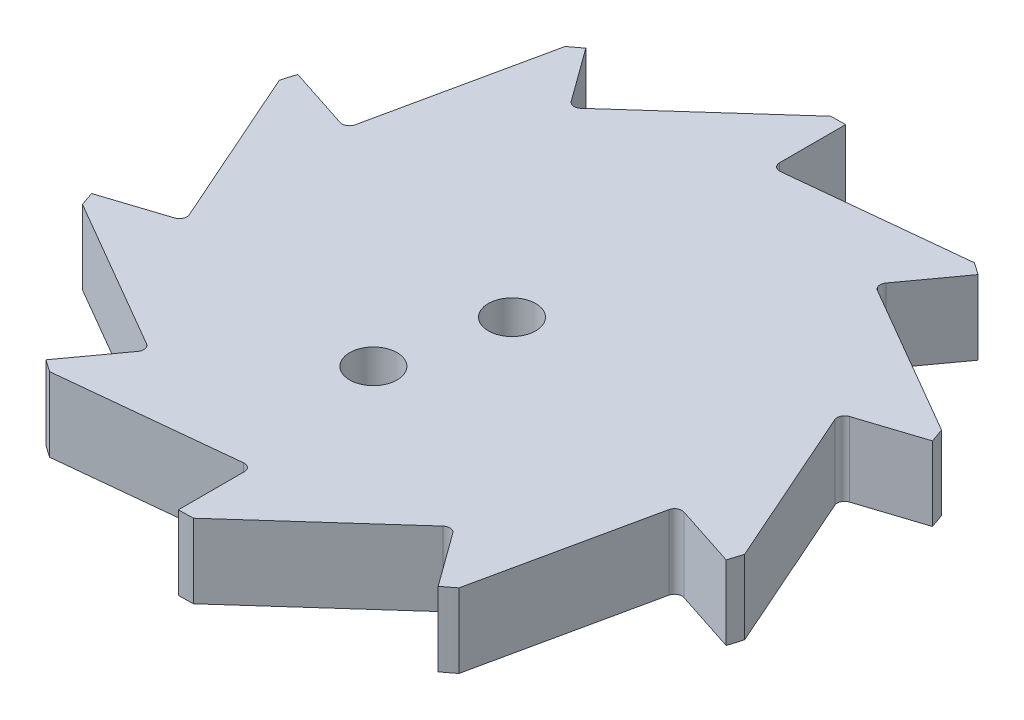
SolidWorks part; units mm, degrees
ref_plane "Front Plane" through (0, 0, 0) normal (0, 0, 1) x (1, 0, 0)
ref_plane "Top Plane" through (0, 0, 0) normal (0, 1, 0) x (1, 0, 0)
ref_plane "Right Plane" through (0, 0, 0) normal (1, 0, 0) x (0, 0, -1)
sketch "Sketch2" plane through (0, 0, 0) normal (0, 1, 0) x (1, 0, 0)
  line L0 (0, 35) -> (0, 45)
  line L1 (-20.5725, 28.3156) -> (0, 0) construction
  line L2 (0, 0) -> (0, 49.5121) construction
  line L3 (-20.5725, 28.3156) -> (-2, 44.9555)
  line L4 (20.5725, 28.3156) -> (26.4503, 36.4058)
  line L5 (0, 35) -> (24.8062, 37.5454)
  line L6 (33.287, 10.8156) -> (42.7975, 13.9058)
  line L7 (20.5725, 28.3156) -> (42.1372, 15.7941)
  line L8 (33.287, -10.8156) -> (42.7975, -13.9058)
  line L9 (33.287, 10.8156) -> (43.3733, -11.9899)
  line L10 (20.5725, -28.3156) -> (26.4503, -36.4058)
  line L11 (33.287, -10.8156) -> (28.0422, -35.1942)
  line L12 (0, -35) -> (0, -45)
  line L13 (20.5725, -28.3156) -> (2, -44.9555)
  line L14 (-20.5725, -28.3156) -> (-26.4503, -36.4058)
  line L15 (0, -35) -> (-24.8062, -37.5454)
  line L16 (-33.287, -10.8156) -> (-42.7975, -13.9058)
  line L17 (-20.5725, -28.3156) -> (-42.1372, -15.7941)
  line L18 (-33.287, 10.8156) -> (-42.7975, 13.9058)
  line L19 (-33.287, -10.8156) -> (-43.3733, 11.9899)
  line L20 (-20.5725, 28.3156) -> (-26.4503, 36.4058)
  line L21 (-33.287, 10.8156) -> (-28.0422, 35.1942)
  circle A0 centre (0, 0) radius 35
  arc A1 (-2, 44.9555) -> (26.4503, 36.4058) centre (0, 0) ccw
  circle A2 centre (0, 0) radius 3.2
  arc A3 (0, 45) -> (-2, 44.9555) centre (0, 0) ccw
  arc A4 (26.4503, 36.4058) -> (0, 45) centre (0, 0) ccw
  arc A5 (42.7975, 13.9058) -> (42.1372, 15.7941) centre (0, 0) ccw
  arc A6 (42.7975, -13.9058) -> (43.3733, -11.9899) centre (0, 0) ccw
  arc A7 (26.4503, -36.4058) -> (28.0422, -35.1942) centre (0, 0) ccw
  arc A8 (0, -45) -> (2, -44.9555) centre (0, 0) ccw
  arc A9 (-26.4503, -36.4058) -> (-24.8062, -37.5454) centre (0, 0) ccw
  arc A10 (-42.7975, -13.9058) -> (-42.1372, -15.7941) centre (0, 0) ccw
  arc A11 (-42.7975, 13.9058) -> (-43.3733, 11.9899) centre (0, 0) ccw
  arc A12 (-26.4503, 36.4058) -> (-28.0422, 35.1942) centre (0, 0) ccw
  dimension "D1" = 70
  dimension "D2" = 90
  dimension "D5" = 6.4
  dimension "D3" = 36
  dimension "D6" = 2
  dimension "D4" = 10
extrude "Boss-Extrude1" add sketch "Sketch2" along normal blind 10
fillet "Fillet1" radius 1 10 edges at (-33.287, 5, -10.8156) (20.5725, 5, -28.3156) (33.287, 5, -10.8156) (33.287, 5, 10.8156) (20.5725, 5, 28.3156) (0, 5, 35) (-20.5725, 5, 28.3156) (-33.287, 5, 10.8156) (-20.5725, 5, -28.3156) (0, 5, -35)
extrude "Cut-Extrude1" cut sketch "Sketch3" against normal blind 40
sketch "Sketch3" plane through (352.7705, 10, -1092.5267) normal (0, 1, 0) x (-0.9456, 0, 0.3254)
  circle A0 centre (697.367, 931.3924) radius 3.2
